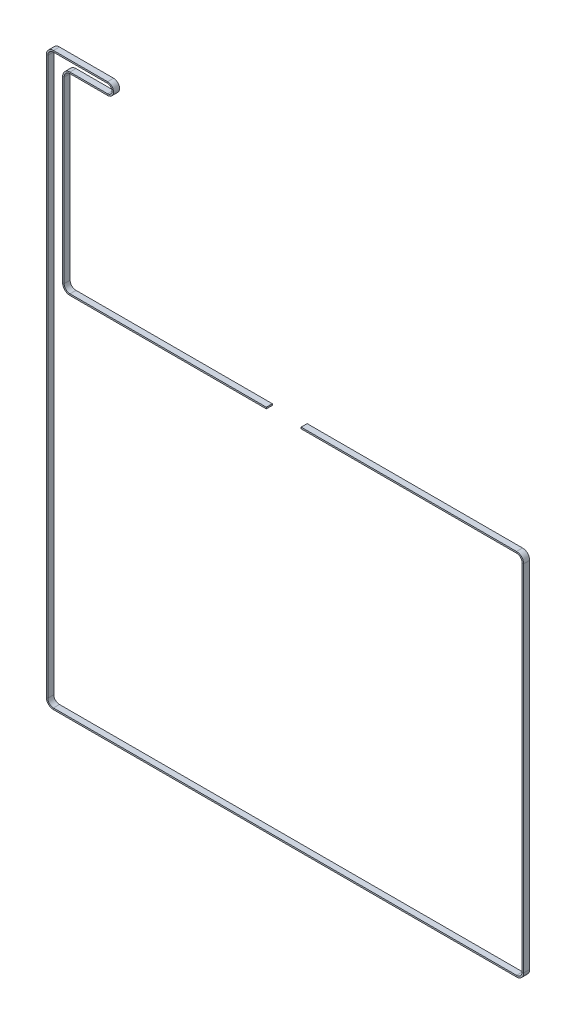
SolidWorks part; units mm, degrees
ref_plane "Front" through (0, 0, 0) normal (0, 0, 1) x (1, 0, 0)
ref_plane "Top" through (0, 0, 0) normal (0, 1, 0) x (1, 0, 0)
ref_plane "Right" through (0, 0, 0) normal (1, 0, 0) x (0, 0, -1)
sketch "Sketch1" plane through (0, -21, 4.45) normal (0, 0, 1) x (1, 0, 0)
  line L0 (10, 63.3) -> (47.5, 63.3)
  line L1 (47.5, 73.7) -> (-6.5, 73.7)
  line L2 (-12.875, 67.325) -> (-12.875, -488)
  line L3 (-6.5, -494.375) -> (455.5, -494.375)
  line L4 (461.875, -488) -> (461.875, -134.5443)
  line L5 (455.5, -128.1693) -> (240.5906, -128.1693)
  line L7 (3.4, 56.7) -> (3.4, -121.7193)
  line L8 (10, -128.3193) -> (205.8906, -128.3193)
  line L10 (205.8906, -128.2193) -> (205.8906, -131.7193) construction
  line L11 (240.5906, -127.7193) -> (240.5906, -120.7193) construction
  circle A0 centre (47.5, 68.5) radius 5.2 construction
  circle A1 centre (10, 56.7) radius 6.6 construction
  circle A2 centre (-6.5, 67.325) radius 6.375 construction
  circle A3 centre (10, -121.7193) radius 6.6 construction
  circle A4 centre (-6.5, -488) radius 6.375 construction
  circle A5 centre (455.5, -488) radius 6.375 construction
  circle A6 centre (455.5, -134.5443) radius 6.375 construction
  arc A7 (47.5, 73.7) -> (47.5, 63.3) centre (47.5, 68.5) cw
  arc A8 (10, 63.3) -> (3.4, 56.7) centre (10, 56.7) ccw
  arc A9 (-12.875, 67.325) -> (-6.5, 73.7) centre (-6.5, 67.325) cw
  arc A10 (-6.5, -494.375) -> (-12.875, -488) centre (-6.5, -488) cw
  arc A11 (455.5, -494.375) -> (461.875, -488) centre (455.5, -488) ccw
  arc A12 (461.875, -134.5443) -> (455.5, -128.1693) centre (455.5, -134.5443) ccw
  arc A13 (3.4, -121.7193) -> (10, -128.3193) centre (10, -121.7193) ccw
  circle A14 centre (-6.5, 67.325) radius 9 construction
  dimension "D1" = 12.75
ref_plane "Plane1" through (240.5906, -149.1693, 4.45) normal (-1, 0, 0) x (0, 0, 1)
sketch "Sketch2" plane through (240.5906, -149.1693, 4.45) normal (-1, 0, 0) x (0, 0, 1)
  line L1 (-3, 0.75) -> (3, 0.75)
  line L2 (-3, 0.75) -> (-3, -0.75)
  line L3 (-3, -0.75) -> (3, -0.75)
  line L4 (3, 0.75) -> (3, -0.75)
  line L5 (-3, 0.75) -> (3, -0.75) construction
  line L6 (-3, -0.75) -> (3, 0.75) construction
  point P0 (0, 0)
  dimension "D1" = 6
  dimension "D2" = 1.5
sweep "Sweep1" add profiles "Sketch2" path "Sketch1"
